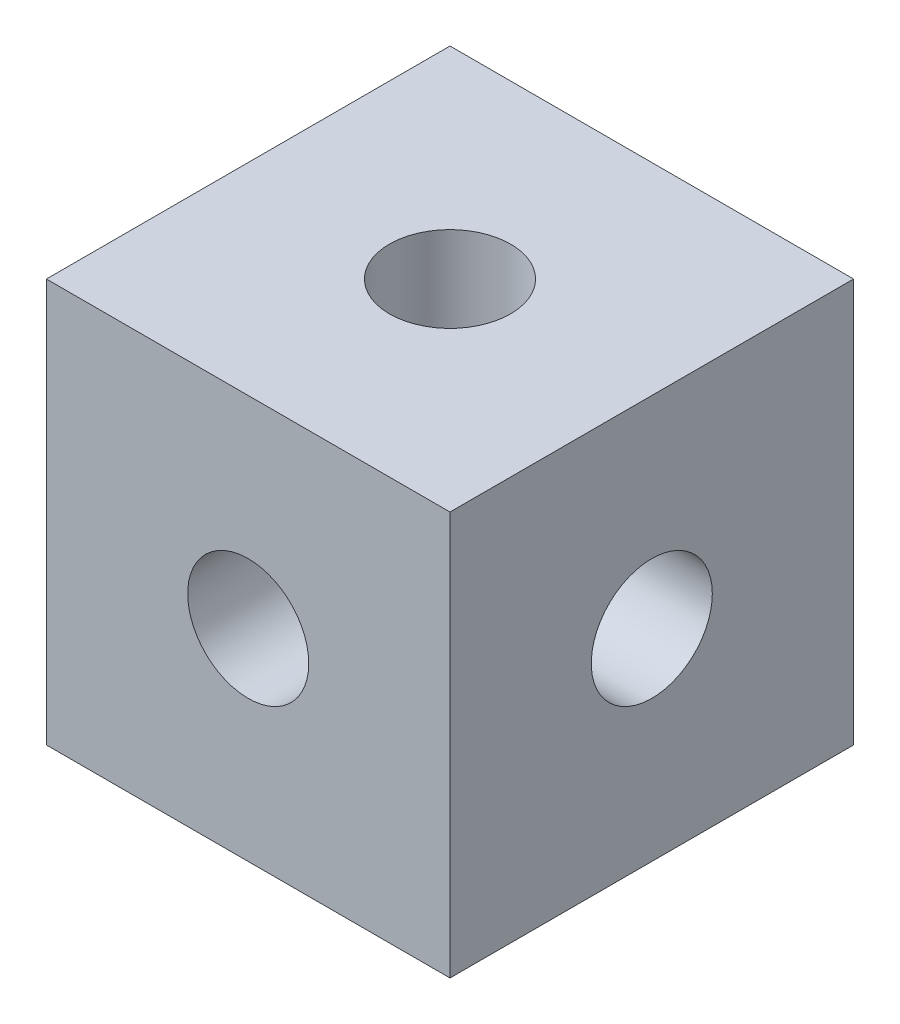
SolidWorks part; units mm, degrees
ref_plane "前视基准面" through (0, 0, 0) normal (0, 0, 1) x (1, 0, 0)
ref_plane "上视基准面" through (0, 0, 0) normal (0, 1, 0) x (1, 0, 0)
ref_plane "右视基准面" through (0, 0, 0) normal (1, 0, 0) x (0, 0, -1)
sketch "草图1" plane through (0, 0, 0) normal (0, 0, 1) x (1, 0, 0)
  line L1 (0, 0) -> (10, 0)
  line L2 (0, 0) -> (0, 10)
  line L3 (0, 10) -> (10, 10)
  line L4 (10, 0) -> (10, 10)
  dimension "D1" = 10
  dimension "D2" = 10
extrude "凸台-拉伸1" add sketch "草图1" along normal blind 10
sketch "草图2" plane through (0, 10, 0) normal (0, 1, 0) x (1, 0, 0)
  line L0 (5, 0) -> (5, -10) construction
  line L1 (10, 0) -> (0, 0) construction
  line L2 (10, -10) -> (0, -10) construction
  line L3 (0, -5) -> (10, -5) construction
  line L4 (0, -10) -> (0, 0) construction
  line L5 (10, -10) -> (10, 0) construction
  circle A0 centre (5, -5) radius 1.5
  dimension "D1" = 3
extrude "切除-拉伸1" cut sketch "草图2" against normal blind 10
sketch "草图3" plane through (10, 0, 0) normal (1, 0, 0) x (0, 0, -1)
  line L0 (0, 0) -> (0, 10) construction
  line L1 (-10, 10) -> (0, 10) construction
  circle A0 centre (-5, 5) radius 1.5
  dimension "D1" = 3
  dimension "D2" = 5
  dimension "D3" = 5
extrude "切除-拉伸2" cut sketch "草图3" against normal blind 10
sketch "草图4" plane through (0, 0, 10) normal (0, 0, 1) x (1, 0, 0)
  line L0 (10, 0) -> (10, 10) construction
  line L1 (10, 10) -> (0, 10) construction
  circle A0 centre (5, 5) radius 1.5
  dimension "D1" = 3
  dimension "D2" = 5
  dimension "D3" = 5
extrude "切除-拉伸3" cut sketch "草图4" against normal blind 10
